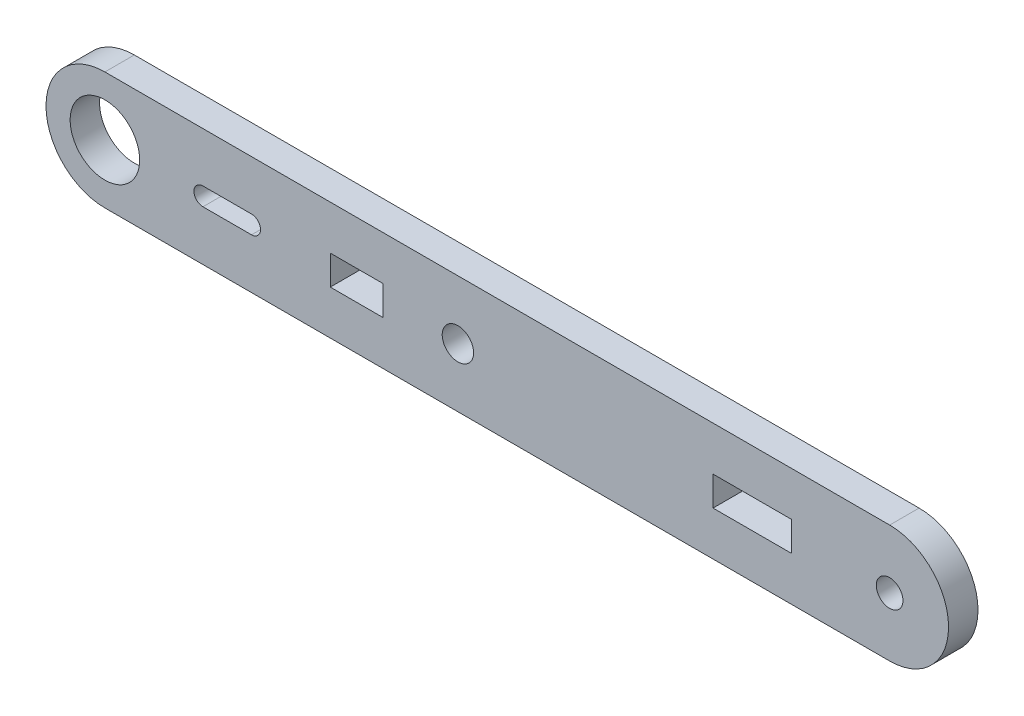
SolidWorks part; units mm, degrees
ref_plane "前视基准面" through (0, 0, 0) normal (0, 0, 1) x (1, 0, 0)
ref_plane "上视基准面" through (0, 0, 0) normal (0, 1, 0) x (1, 0, 0)
ref_plane "右视基准面" through (0, 0, 0) normal (1, 0, 0) x (0, 0, -1)
ref_plane "基准面4" through (0, 0, 3) normal (0, 0, 1) x (1, 0, 0)
sketch "草图1" plane through (0, 0, 3) normal (0, 0, 1) x (1, 0, 0)
  line L0 (-26.3778, 7.4995) -> (-21.005, 7.4995)
  line L1 (-21.005, 7.4995) -> (-21.005, 4.4994)
  line L2 (-21.005, 4.4994) -> (-26.3778, 4.4994)
  line L3 (-26.3778, 4.4994) -> (-26.3778, 7.4995)
  line L4 (12.6221, 7.4995) -> (20.6213, 7.4995)
  line L5 (20.6213, 7.4995) -> (20.6213, 4.4994)
  line L6 (20.6213, 4.4994) -> (12.6221, 4.4994)
  line L7 (12.6221, 4.4994) -> (12.6221, 7.4995)
  line L8 (30.6182, 12) -> (-49.3435, 12)
  line L9 (-49.3435, 0) -> (30.6182, 0)
  line L10 (-34.4047, 5.1001) -> (-39.3523, 5.1001)
  line L11 (-39.3523, 6.9343) -> (-34.4047, 6.9343)
  arc A0 (-49.3435, 12) -> (-49.3435, 0) centre (-49.3435, 6) ccw
  arc A1 (30.6182, 0) -> (30.6182, 12) centre (30.6182, 6) ccw
  circle A2 centre (30.6116, 6.0001) radius 1.3576
  circle A3 centre (-13.3753, 6.0002) radius 1.3576
  circle A4 centre (-49.3435, 6) radius 3.5438
  arc A5 (-34.4047, 6.9343) -> (-34.4047, 5.1001) centre (-34.4047, 6.0172) cw
  arc A6 (-39.3523, 5.1001) -> (-39.3523, 6.9343) centre (-39.3523, 6.0172) cw
extrude "凸台-拉伸1" add sketch "草图1" against normal blind 3
sketch "草图2" plane through (0, 0, 3) normal (0, 0, 1) x (1, 0, 0)
  circle A0 centre (-13.3753, 6.0002) radius 1.6
  dimension "D1" = 3.2
extrude "切除-拉伸1" cut sketch "草图2" against normal through all
